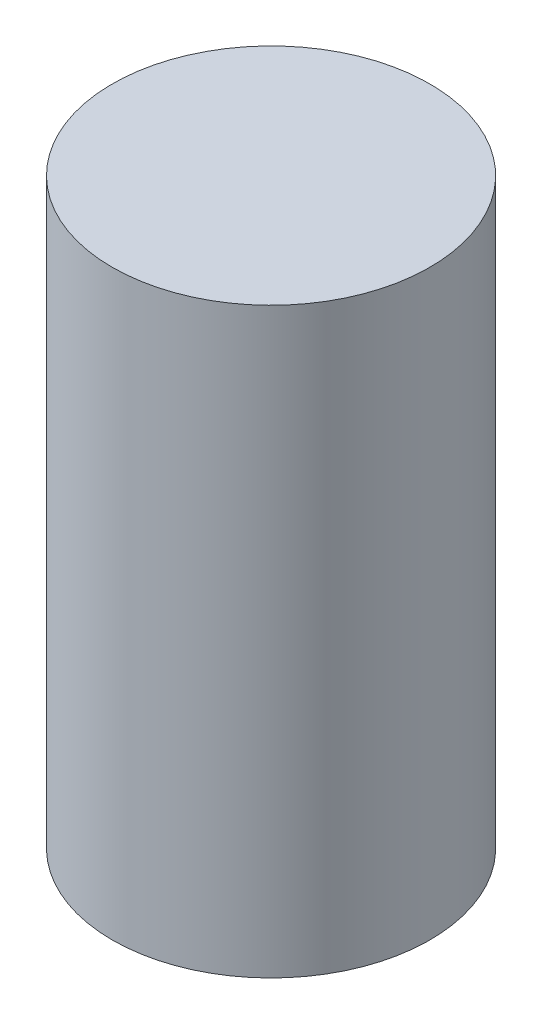
SolidWorks part; units mm, degrees
ref_plane "Front Plane" through (0, 0, 0) normal (0, 0, 1) x (1, 0, 0)
ref_plane "Top Plane" through (0, 0, 0) normal (0, 1, 0) x (1, 0, 0)
ref_plane "Right Plane" through (0, 0, 0) normal (1, 0, 0) x (0, 0, -1)
sketch "Sketch1" plane through (0, 0, 0) normal (0, 1, 0) x (1, 0, 0)
  circle A0 centre (0, 0) radius 19
extrude "Boss-Extrude1" add sketch "Sketch1" along normal blind 69.7
